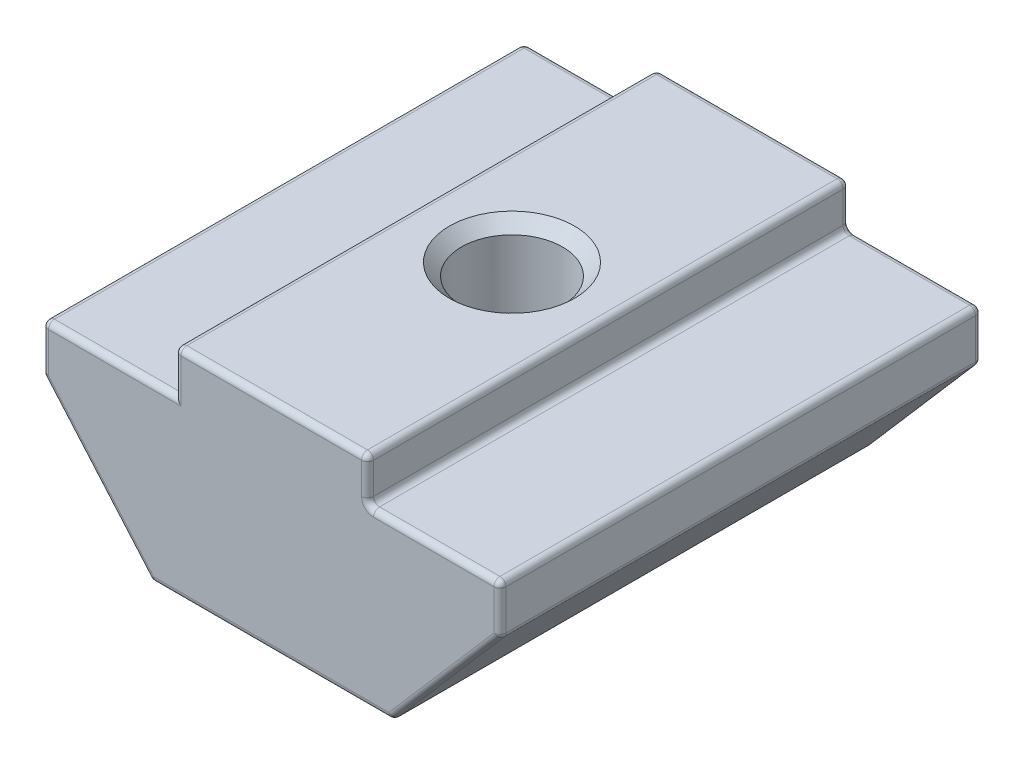
SolidWorks part; units mm, degrees
ref_plane "Front Plane" through (0, 0, 0) normal (0, 0, 1) x (1, 0, 0)
ref_plane "Top Plane" through (0, 0, 0) normal (0, 1, 0) x (1, 0, 0)
ref_plane "Right Plane" through (0, 0, 0) normal (1, 0, 0) x (0, 0, -1)
sketch "Sketch1" plane through (0, 0, 0) normal (0, 0, 1) x (1, 0, 0)
  line L0 (-4, 0) -> (4, 0)
  line L1 (4, 0) -> (4, -1.8)
  line L2 (4, -1.8) -> (9.5, -1.8)
  line L3 (9.5, -1.8) -> (9.5, -3.8)
  line L4 (9.5, -3.8) -> (5, -9)
  line L5 (0, 0) -> (0, -9) construction
  line L6 (-9.5, -3.8) -> (-5, -9)
  line L7 (-9.5, -1.8) -> (-9.5, -3.8)
  line L8 (-4, -1.8) -> (-9.5, -1.8)
  line L9 (-4, 0) -> (-4, -1.8)
  line L10 (-5, -9) -> (5, -9)
  point P4 (0, 0)
  dimension "D1" = 9
  dimension "D2" = 19
  dimension "D3" = 8
  dimension "D4" = 10
  dimension "D5" = 2
  dimension "D6" = 1.8
extrude "Boss-Extrude1" add sketch "Sketch1" along normal blind 20
sketch "Sketch2" plane through (0, 0, 0) normal (0, 1, 0) x (1, 0, 0)
  line L0 (0, 0) -> (0, -20) construction
  line L1 (4, -20) -> (-4, -20) construction
hole_wizard "M5x0.8 Tapped Hole1" positions "Sketch3" profile "Sketch4" tap size "M5x0.8" standard "ANSI Metric" end condition through all
sketch "Sketch3" plane through (0, 0, 0) normal (0, 1, 0) x (1, 0, 0)
  line L0 (0, 0) -> (0, -20) construction
  point P0 (0, -10)
sketch "Sketch4" plane through (0, 0, 10) normal (1, 0, 0) x (0, 0, 1)
  line L0 (0, 0) -> (0, 9)
  line L1 (0, 9) -> (2.1, 9)
  line L2 (2.1, 9) -> (2.1, 0)
  line L5 (2.1, 0) -> (0, 0)
  line L11 (0, -6.35) -> (0, 107.95) construction
  dimension "Thru Tap Drill Dia." = 4.2
  dimension "Thru Tap Drill Depth" = 9
cosmetic thread "Hole Thread1" parameters "D2"=5
chamfer "Chamfer1" distance 0.5 2 edges at (0, -9, 12.1) (0, 0, 12.1)
fillet "Fillet1" radius 0.25 29 edges at (-9.5, -1.8, 10) (-9.5, -3.8, 10) (9.5, -3.8, 10) (9.5, -1.8, 10) (0, 0, 0) (-4, -0.9, 0) (-6.75, -1.8, 0) (-9.5, -2.8, 0) (-7.25, -6.4, 0) (0, -9, 0) (7.25, -6.4, 0) (9.5, -2.8, 0) (6.75, -1.8, 0) (4, -0.9, 0) (6.75, -1.8, 20) (9.5, -2.8, 20) (7.25, -6.4, 20) (0, -9, 20) (-7.25, -6.4, 20) (-9.5, -2.8, 20) (-6.75, -1.8, 20) (-4, -0.9, 20) (0, 0, 20) (4, -0.9, 20) (5, -9, 10) (-5, -9, 10) (4, -1.8, 10) (-4, 0, 10) (4, 0, 10)
